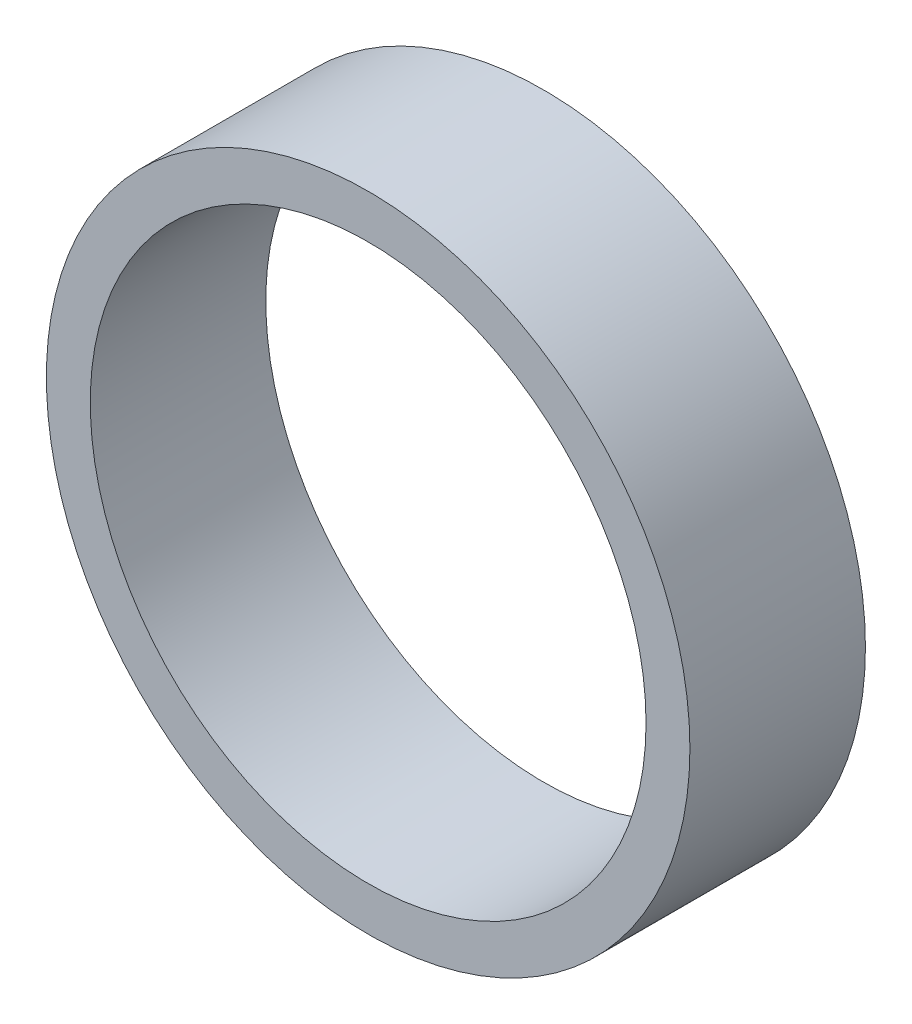
SolidWorks part; units mm, degrees
ref_plane "Front Plane" through (0, 0, 0) normal (0, 0, 1) x (1, 0, 0)
ref_plane "Top Plane" through (0, 0, 0) normal (0, 1, 0) x (1, 0, 0)
ref_plane "Right Plane" through (0, 0, 0) normal (1, 0, 0) x (0, 0, -1)
sketch "Sketch1" plane through (0, 0, 0) normal (0, 0, 1) x (1, 0, 0)
  circle A0 centre (0, 0) radius 11
  circle A1 centre (0, 0) radius 9.5
  dimension "D1" = 22
  dimension "D2" = 19
extrude "Boss-Extrude1" add sketch "Sketch1" along normal blind 6
